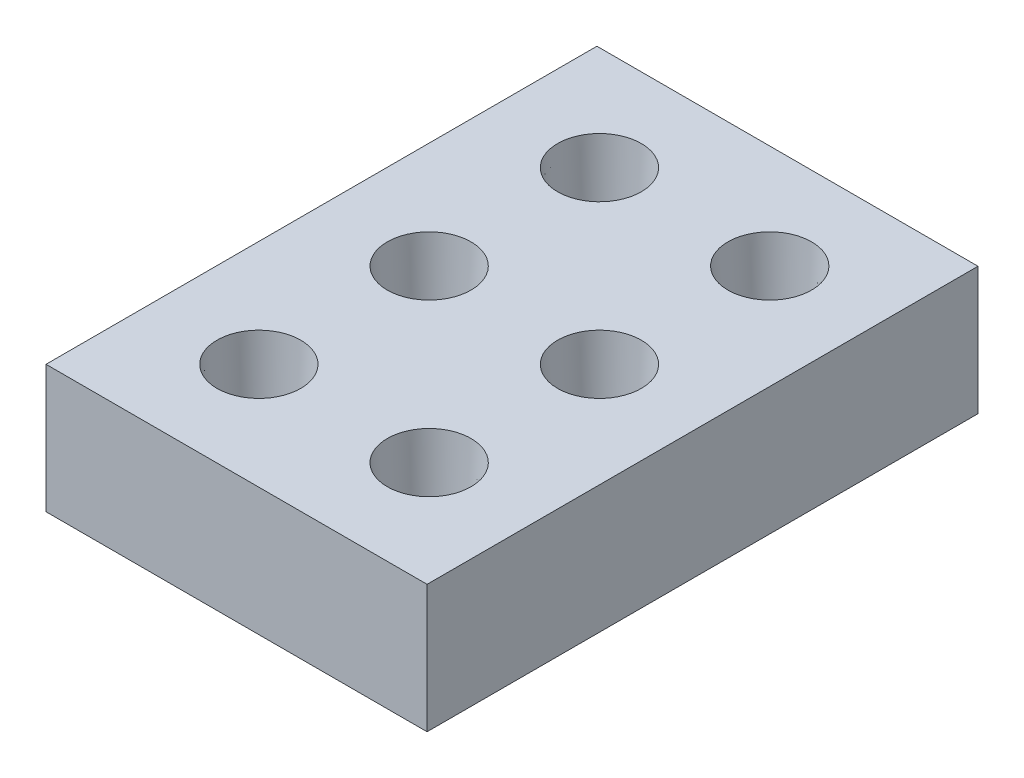
SolidWorks part; units mm, degrees
ref_plane "Front Plane" through (0, 0, 0) normal (0, 0, 1) x (1, 0, 0)
ref_plane "Top Plane" through (0, 0, 0) normal (0, 1, 0) x (1, 0, 0)
ref_plane "Right Plane" through (0, 0, 0) normal (1, 0, 0) x (0, 0, -1)
sketch "Sketch1" plane through (0, 0, 0) normal (0, 1, 0) x (1, 0, 0)
  line L0 (-5, 0) -> (12.9024, 0)
  line L1 (-5, 0) -> (-5, 25.8806)
  line L2 (-5, 25.8806) -> (12.9024, 25.8806)
  line L3 (12.9024, 0) -> (12.9024, 25.8806)
  point P4 (0, 0)
  point P6 (0, 0)
  point P7 (20.1499, 0)
  dimension "D1" = 17.9024
  dimension "D2" = 25.8806
  dimension "D3" = 5
extrude "Boss-Extrude1" add sketch "Sketch1" along normal blind 6
sketch "Sketch3" plane through (0, 0, 0) normal (-1, 0, 0) x (0, 0, 1)
  line L0 (-5, 6) -> (-5, 0)
  line L1 (-25.8806, 6) -> (0, 6) construction
  line L2 (-25.8806, 0) -> (0, 0) construction
  line L3 (-5, 0) -> (-6.77, 0)
  line L4 (-6.77, 0) -> (-6.77, 3.2)
  line L5 (-6.77, 3.2) -> (-6.9658, 6)
  line L6 (-6.9658, 6) -> (-5, 6)
  line L7 (0, 6) -> (0, 0) construction
  dimension "D1" = 1.77
  dimension "D2" = 2.8
  dimension "D3" = 176
  dimension "D4" = 5
revolve "Cut-Revolve1" cut sketch "Sketch3" angle 360 about L0
pattern_linear "LPattern1" count 3 spacing 8 along (0, 0, -1) count 2 spacing 8 along (1, 0, 0) of "Cut-Revolve1"
